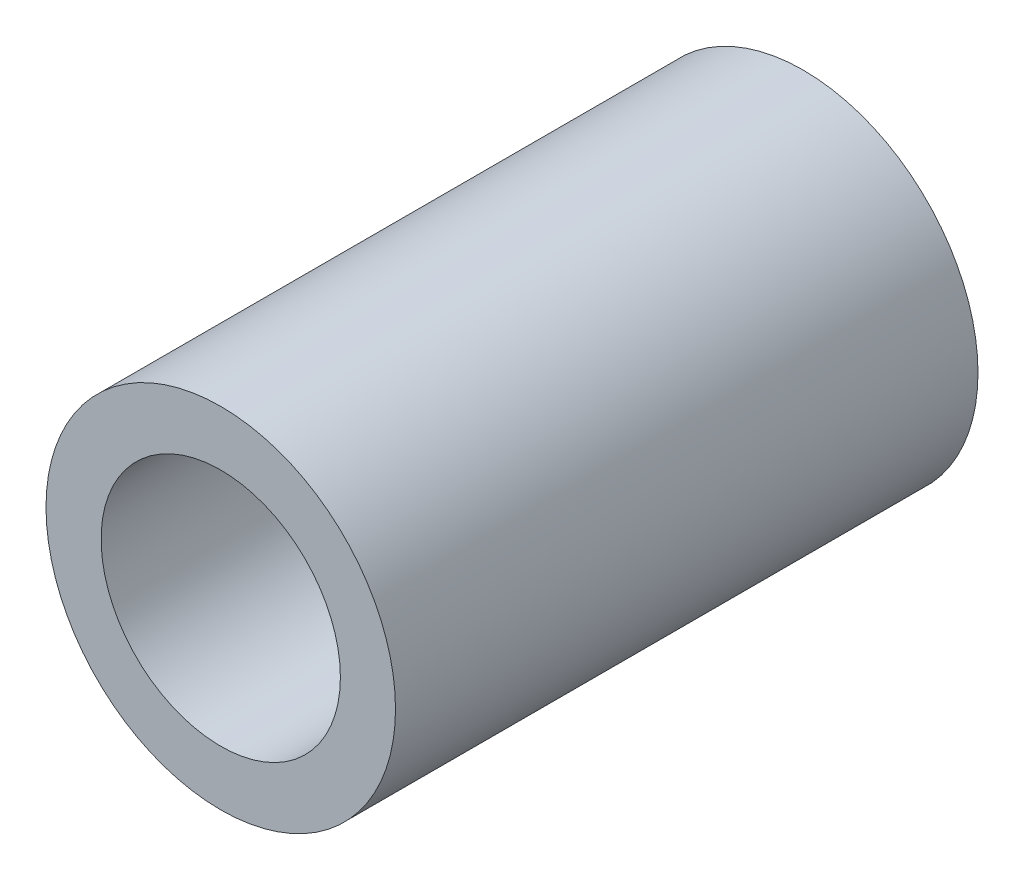
SolidWorks part; units mm, degrees
ref_plane "Front Plane" through (0, 0, 0) normal (0, 0, 1) x (1, 0, 0)
ref_plane "Top Plane" through (0, 0, 0) normal (0, 1, 0) x (1, 0, 0)
ref_plane "Right Plane" through (0, 0, 0) normal (1, 0, 0) x (0, 0, -1)
sketch "Sketch1" plane through (0, 0, 0) normal (0, 0, 1) x (1, 0, 0)
  circle A0 centre (0, 0) radius 7.5
  circle A1 centre (0, 0) radius 5.135
  dimension "D1" = 10.27
  dimension "D2" = 15
extrude "Boss-Extrude1" add sketch "Sketch1" along normal blind 25
